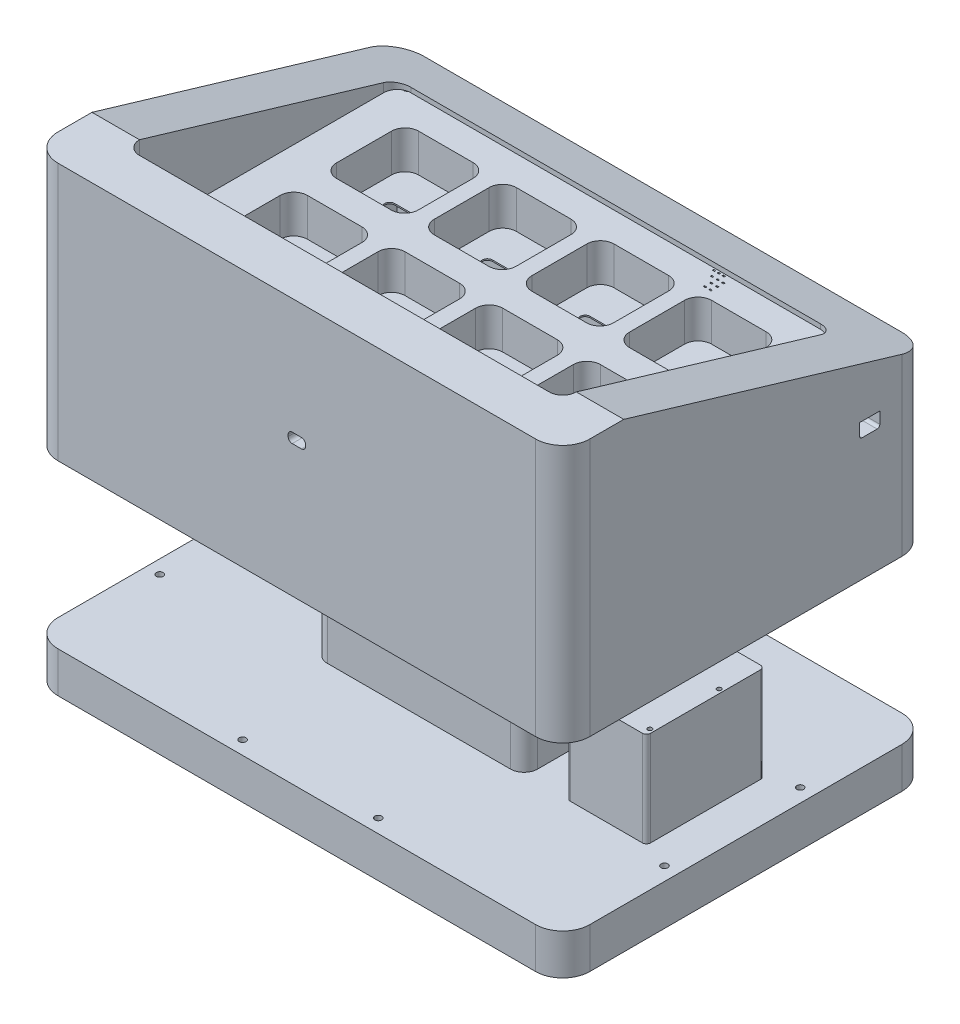
SolidWorks part; units mm, degrees
ref_plane "Front Plane" through (0, 0, 0) normal (0, 0, 1) x (1, 0, 0)
ref_plane "Top Plane" through (0, 0, 0) normal (0, 1, 0) x (1, 0, 0)
ref_plane "Right Plane" through (0, 0, 0) normal (1, 0, 0) x (0, 0, -1)
sketch "Sketch2" plane through (0, 0, 0) normal (0, 1, 0) x (1, 0, 0)
  line L0 (-196, -135) -> (-61, -135)
  line L1 (-196, 135) -> (196, 135)
  line L2 (-196, 135) -> (-196, -135)
  line L3 (-196, -135) -> (196, -135)
  line L4 (196, 135) -> (196, -135)
  line L5 (-196, 135) -> (196, -135) construction
  line L6 (-196, -135) -> (196, 135) construction
  point P0 (0, 0)
  dimension "D1" = 392
  dimension "D2" = 270
  dimension "D3" = 135
extrude "Boss-Extrude1" add sketch "Sketch2" along normal blind 30
sketch "Sketch3" plane through (0, 30, 0) normal (0, 1, 0) x (1, 0, 0)
  line L4 (-196, 135) -> (-196, -135) construction
  line L5 (-196, -30) -> (-196, -135)
  line L6 (-196, -135) -> (-23.5, -135) construction
  line L7 (-196, -135) -> (196, -135) construction
  line L12 (-23.5, -135) -> (-23.5, -85) construction
  line L16 (-77.5, 45) -> (77.5, 45)
  line L17 (-77.5, 45) -> (-77.5, -45)
  line L18 (-77.5, -45) -> (77.5, -45)
  line L19 (77.5, 45) -> (77.5, -45)
  line L20 (-77.5, 45) -> (77.5, -45) construction
  line L21 (-77.5, -45) -> (77.5, 45) construction
  point P5 (0, 0)
  dimension "D1" = 172.5
  dimension "D2" = 155
  dimension "D3" = 50
  dimension "D4" = 90
extrude "Boss-Extrude2" add sketch "Sketch3" along normal blind 70 contours L17 L18 L19 L16
ref_plane "Plane1" through (0, 150, 0) normal (0, 1, 0) x (1, 0, 0)
sketch "Sketch15" plane through (0, 150, 0) normal (0, 1, 0) x (1, 0, 0)
  line L1 (-178.4314, 128.826) -> (178.4314, 128.826)
  line L2 (-178.4314, 128.826) -> (-178.4314, -128.826)
  line L3 (-178.4314, -128.826) -> (178.4314, -128.826)
  line L4 (178.4314, 128.826) -> (178.4314, -128.826)
  line L5 (-178.4314, 128.826) -> (178.4314, -128.826) construction
  line L6 (-178.4314, -128.826) -> (178.4314, 128.826) construction
  point P0 (0, 0)
sketch "Sketch17" plane through (0, 150, 0) normal (0, 1, 0) x (1, 0, 0)
  line L1 (-196, 135) -> (196, 135)
  line L2 (-196, 135) -> (-196, -135)
  line L3 (-196, -135) -> (196, -135)
  line L4 (196, 135) -> (196, -135)
  line L5 (-196, 135) -> (196, -135) construction
  line L6 (-196, -135) -> (196, 135) construction
  point P0 (0, 0)
  dimension "D1" = 392
  dimension "D2" = 270
extrude "Boss-Extrude3" add sketch "Sketch17" along normal blind 190 separate body
sketch "Sketch18" plane through (-196, 0, 0) normal (-1, 0, 0) x (0, 0, 1)
  line L0 (-135.2725, 210.3629) -> (3.9225, 185.819) construction
  line L1 (-135, 340) -> (135, 340) construction
  dimension "D1" = 10
sketch "Sketch19" plane through (-196, 0, 0) normal (-1, 0, 0) x (0, 0, 1)
  line L0 (-135, 340) -> (135, 316.3781)
  line L1 (135, 340) -> (135, 150) construction
  line L2 (135, 316.3781) -> (135, 340)
  line L3 (135, 340) -> (-135, 340)
  dimension "D1" = 5
fillet "Fillet4" radius 20 4 edges at (-196, 245, 135) (196, 245, 135) (196, 245, -135) (-196, 245, -135)
sketch "Sketch41" plane through (0, 0, 0) normal (0, -1, 0) x (1, 0, 0)
  line L0 (0, -135) -> (0, -138.1967) construction
  line L1 (-196, -135) -> (196, -135) construction
sketch "Sketch44" plane through (0, 0, 0) normal (0, -1, 0) x (1, 0, 0)
  line L0 (0, 0) -> (196, 0) construction
  line L1 (196, 115) -> (196, -115) construction
  line L2 (196, 0) -> (-196, 0) construction
  line L3 (-196, -135.2725) -> (-196, 3.9225) construction
  line L4 (0, 135) -> (0, -138.1967) construction
  line L5 (-176, 135) -> (176, 135) construction
sketch "Sketch66" plane through (-196, 0, 0) normal (-1, 0, 0) x (0, 0, 1)
  line L1 (-115, 309.6214) -> (115, 309.6214)
  line L2 (-115, 309.6214) -> (-115, 150)
  line L3 (-115, 150) -> (115, 150)
  line L4 (115, 309.6214) -> (115, 150)
  line L5 (-115, 309.6214) -> (115, 150) construction
  line L6 (-115, 150) -> (115, 309.6214) construction
  point P0 (0, 229.8107)
sketch "Sketch68" plane through (196, 0, 0) normal (1, 0, 0) x (0, 0, -1)
  line L1 (-115, 309.6214) -> (115, 309.6214)
  line L2 (-115, 309.6214) -> (-115, 150)
  line L3 (-115, 150) -> (115, 150)
  line L4 (115, 309.6214) -> (115, 150)
  line L5 (-115, 309.6214) -> (115, 150) construction
  line L6 (-115, 150) -> (115, 309.6214) construction
  point P0 (0, 229.8107)
fillet "Fillet5" radius 10 4 edges at (77.5, 65, 45) (77.5, 65, -45) (-77.5, 65, -45) (-77.5, 65, 45)
sketch "Sketch71" plane through (0, 340, 0) normal (0, 1, 0) x (1, 0, 0)
  line L8 (-161, 100) -> (-161, -100)
  line L9 (-161, -100) -> (161, -100)
  line L10 (161, -100) -> (161, 100)
  line L11 (161, 100) -> (-161, 100)
  line L12 (-161, 90) -> (-161, -90)
  line L13 (-151, -100) -> (151, -100)
  line L14 (161, -90) -> (161, 90)
  line L15 (151, 100) -> (-151, 100)
  arc A4 (-161, -90) -> (-151, -100) centre (-151, -90) ccw
  arc A5 (151, -100) -> (161, -90) centre (151, -90) ccw
  arc A6 (161, 90) -> (151, 100) centre (151, 90) ccw
  arc A7 (-161, 90) -> (-151, 100) centre (-151, 90) cw
  dimension "D2" = 10
  dimension "D1" = 35
extrude "Cut-Extrude1" cut sketch "Sketch71" against normal blind 60
sketch "PCB" plane through (0, 280, 0) normal (0, 1, 0) x (1, 0, 0)
  line L1 (-160, 107.5) -> (160, 107.5)
  line L2 (-160, 107.5) -> (-160, -107.5)
  line L3 (-160, -107.5) -> (160, -107.5)
  line L4 (160, 107.5) -> (160, -107.5)
  line L5 (-160, 107.5) -> (160, -107.5) construction
  line L6 (-160, -107.5) -> (160, 107.5) construction
  point P0 (0, 0)
  dimension "D1" = 320
  dimension "D2" = 215
sketch "Sketch73" plane through (0, 280, 0) normal (0, 1, 0) x (1, 0, 0)
  line L0 (-160, -107.5) -> (-160, -33.357) construction
  line L1 (-160, 107.5) -> (-160, -107.5) construction
  line L2 (-160, -33.357) -> (-110.75, -33.357) construction
  line L3 (-110.75, -33.357) -> (-107, -33.357) construction
  line L4 (-107, -33.357) -> (-96.4, -33.357) construction
  line L5 (-107, -33.357) -> (-117.6, -33.357) construction
  line L6 (-96.4, -33.357) -> (-99.83, -33.357) construction
  line L7 (-117.6, -33.357) -> (-114.17, -33.357) construction
  line L8 (-42.17, -29.627) -> (-27.83, -29.627)
  line L11 (-114.17, -29.627) -> (-99.83, -29.627)
  line L12 (-114.17, -37.087) -> (-99.83, -37.087)
  line L13 (-42.17, -37.087) -> (-27.83, -37.087)
  line L14 (29.83, -29.627) -> (44.17, -29.627)
  line L15 (29.83, -37.087) -> (44.17, -37.087)
  line L16 (101.83, -29.627) -> (116.17, -29.627)
  line L17 (101.83, -37.087) -> (116.17, -37.087)
  line L18 (-114.17, -33.357) -> (-114.17, 7.143) construction
  line L19 (-114.17, 7.143) -> (-161, 7.143) construction
  line L20 (-161, 90) -> (-161, -90) construction
  line L21 (-161, 7.143) -> (161, 7.143) construction
  line L22 (161, -90) -> (161, 90) construction
  line L23 (101.83, 51.373) -> (116.17, 51.373)
  line L24 (101.83, 43.913) -> (116.17, 43.913)
  line L25 (29.83, 51.373) -> (44.17, 51.373)
  line L26 (29.83, 43.913) -> (44.17, 43.913)
  line L27 (-42.17, 51.373) -> (-27.83, 51.373)
  line L28 (-42.17, 43.913) -> (-27.83, 43.913)
  line L29 (-114.17, 51.373) -> (-99.83, 51.373)
  line L30 (-114.17, 43.913) -> (-99.83, 43.913)
  arc A4 (-99.83, -37.087) -> (-99.83, -29.627) centre (-99.83, -33.357) ccw
  arc A5 (-114.17, -29.627) -> (-114.17, -37.087) centre (-114.17, -33.357) ccw
  arc A6 (-27.83, -37.087) -> (-27.83, -29.627) centre (-27.83, -33.357) ccw
  arc A7 (-42.17, -29.627) -> (-42.17, -37.087) centre (-42.17, -33.357) ccw
  arc A8 (44.17, -37.087) -> (44.17, -29.627) centre (44.17, -33.357) ccw
  arc A9 (29.83, -29.627) -> (29.83, -37.087) centre (29.83, -33.357) ccw
  arc A10 (116.17, -37.087) -> (116.17, -29.627) centre (116.17, -33.357) ccw
  arc A11 (101.83, -29.627) -> (101.83, -37.087) centre (101.83, -33.357) ccw
  arc A12 (101.83, 43.913) -> (101.83, 51.373) centre (101.83, 47.643) cw
  arc A13 (116.17, 51.373) -> (116.17, 43.913) centre (116.17, 47.643) cw
  arc A14 (29.83, 43.913) -> (29.83, 51.373) centre (29.83, 47.643) cw
  arc A15 (44.17, 51.373) -> (44.17, 43.913) centre (44.17, 47.643) cw
  arc A16 (-42.17, 43.913) -> (-42.17, 51.373) centre (-42.17, 47.643) cw
  arc A17 (-27.83, 51.373) -> (-27.83, 43.913) centre (-27.83, 47.643) cw
  arc A18 (-114.17, 43.913) -> (-114.17, 51.373) centre (-114.17, 47.643) cw
  arc A19 (-99.83, 51.373) -> (-99.83, 43.913) centre (-99.83, 47.643) cw
  dimension "D3" = 4
  dimension "D1" = 74.143
  dimension "D2" = 49.25
  dimension "D4" = 3.75
  dimension "D5" = 10.6
  dimension "D6" = 10.6
  dimension "D7" = 3.43
  dimension "D8" = 3.43
  dimension "D9" = 40.5
sketch "Sketch75" plane through (0, 280, 0) normal (0, 1, 0) x (1, 0, 0)
  line L0 (-117.6, -33.357) -> (-133.6, -33.357) construction
  line L1 (-160, -33.357) -> (-110.75, -33.357) construction
  line L2 (-96.4, -33.357) -> (-73.4, -33.357) construction
  line L4 (-73.4, -33.357) -> (-133.6, -33.357) construction
  line L5 (-107, -29.627) -> (-107, -3.627) construction
  line L10 (-114.17, -29.627) -> (-99.83, -29.627) construction
  line L11 (-107, -37.087) -> (-107, -64.087) construction
  line L12 (-114.17, -37.087) -> (-99.83, -37.087) construction
  line L13 (-73.4, -33.357) -> (-73.4, -13.627)
  line L14 (-83.4, -3.627) -> (-107, -3.627)
  line L15 (-107, -3.627) -> (-123.6, -3.627)
  line L16 (-133.6, -13.627) -> (-133.6, -33.357)
  line L17 (-133.6, -33.357) -> (-133.6, -54.087)
  line L18 (-123.6, -64.087) -> (-107, -64.087)
  line L19 (-107, -64.087) -> (-83.4, -64.087)
  line L20 (-73.4, -54.087) -> (-73.4, -33.357)
  line L21 (-1.4, -54.087) -> (-1.4, -33.357)
  line L22 (-1.4, -33.357) -> (-1.4, -13.627)
  line L23 (-11.4, -3.627) -> (-35, -3.627)
  line L24 (-35, -3.627) -> (-51.6, -3.627)
  line L25 (-61.6, -13.627) -> (-61.6, -33.357)
  line L26 (-61.6, -33.357) -> (-61.6, -54.087)
  line L27 (-51.6, -64.087) -> (-35, -64.087)
  line L28 (-35, -64.087) -> (-11.4, -64.087)
  line L29 (70.6, -54.087) -> (70.6, -33.357)
  line L30 (70.6, -33.357) -> (70.6, -13.627)
  line L31 (60.6, -3.627) -> (37, -3.627)
  line L32 (37, -3.627) -> (20.4, -3.627)
  line L33 (10.4, -13.627) -> (10.4, -33.357)
  line L34 (10.4, -33.357) -> (10.4, -54.087)
  line L35 (20.4, -64.087) -> (37, -64.087)
  line L36 (37, -64.087) -> (60.6, -64.087)
  line L37 (142.6, -54.087) -> (142.6, -33.357)
  line L38 (142.6, -33.357) -> (142.6, -13.627)
  line L39 (132.6, -3.627) -> (109, -3.627)
  line L40 (109, -3.627) -> (92.4, -3.627)
  line L41 (82.4, -13.627) -> (82.4, -33.357)
  line L42 (82.4, -33.357) -> (82.4, -54.087)
  line L43 (92.4, -64.087) -> (109, -64.087)
  line L44 (109, -64.087) -> (132.6, -64.087)
  line L45 (-161, 7.143) -> (161, 7.143) construction
  line L46 (109, 78.373) -> (132.6, 78.373)
  line L47 (92.4, 78.373) -> (109, 78.373)
  line L48 (82.4, 47.643) -> (82.4, 68.373)
  line L49 (82.4, 27.913) -> (82.4, 47.643)
  line L50 (109, 17.913) -> (92.4, 17.913)
  line L51 (132.6, 17.913) -> (109, 17.913)
  line L52 (142.6, 47.643) -> (142.6, 27.913)
  line L53 (142.6, 68.373) -> (142.6, 47.643)
  line L54 (37, 78.373) -> (60.6, 78.373)
  line L55 (20.4, 78.373) -> (37, 78.373)
  line L56 (10.4, 47.643) -> (10.4, 68.373)
  line L57 (10.4, 27.913) -> (10.4, 47.643)
  line L58 (37, 17.913) -> (20.4, 17.913)
  line L59 (60.6, 17.913) -> (37, 17.913)
  line L60 (70.6, 47.643) -> (70.6, 27.913)
  line L61 (70.6, 68.373) -> (70.6, 47.643)
  line L62 (-35, 78.373) -> (-11.4, 78.373)
  line L63 (-51.6, 78.373) -> (-35, 78.373)
  line L64 (-61.6, 47.643) -> (-61.6, 68.373)
  line L65 (-61.6, 27.913) -> (-61.6, 47.643)
  line L66 (-35, 17.913) -> (-51.6, 17.913)
  line L67 (-11.4, 17.913) -> (-35, 17.913)
  line L68 (-1.4, 47.643) -> (-1.4, 27.913)
  line L69 (-1.4, 68.373) -> (-1.4, 47.643)
  line L70 (-107, 78.373) -> (-83.4, 78.373)
  line L71 (-123.6, 78.373) -> (-107, 78.373)
  line L72 (-133.6, 47.643) -> (-133.6, 68.373)
  line L73 (-133.6, 27.913) -> (-133.6, 47.643)
  line L74 (-107, 17.913) -> (-123.6, 17.913)
  line L75 (-83.4, 17.913) -> (-107, 17.913)
  line L76 (-73.4, 47.643) -> (-73.4, 27.913)
  line L77 (-73.4, 68.373) -> (-73.4, 47.643)
  arc A0 (-73.4, -13.627) -> (-83.4, -3.627) centre (-83.4, -13.627) ccw
  arc A1 (-123.6, -3.627) -> (-133.6, -13.627) centre (-123.6, -13.627) ccw
  arc A2 (-133.6, -54.087) -> (-123.6, -64.087) centre (-123.6, -54.087) ccw
  arc A3 (-83.4, -64.087) -> (-73.4, -54.087) centre (-83.4, -54.087) ccw
  arc A4 (-11.4, -64.087) -> (-1.4, -54.087) centre (-11.4, -54.087) ccw
  arc A5 (-1.4, -13.627) -> (-11.4, -3.627) centre (-11.4, -13.627) ccw
  arc A6 (-51.6, -3.627) -> (-61.6, -13.627) centre (-51.6, -13.627) ccw
  arc A7 (-61.6, -54.087) -> (-51.6, -64.087) centre (-51.6, -54.087) ccw
  arc A8 (60.6, -64.087) -> (70.6, -54.087) centre (60.6, -54.087) ccw
  arc A9 (70.6, -13.627) -> (60.6, -3.627) centre (60.6, -13.627) ccw
  arc A10 (20.4, -3.627) -> (10.4, -13.627) centre (20.4, -13.627) ccw
  arc A11 (10.4, -54.087) -> (20.4, -64.087) centre (20.4, -54.087) ccw
  arc A12 (132.6, -64.087) -> (142.6, -54.087) centre (132.6, -54.087) ccw
  arc A13 (142.6, -13.627) -> (132.6, -3.627) centre (132.6, -13.627) ccw
  arc A14 (92.4, -3.627) -> (82.4, -13.627) centre (92.4, -13.627) ccw
  arc A15 (82.4, -54.087) -> (92.4, -64.087) centre (92.4, -54.087) ccw
  arc A16 (132.6, 78.373) -> (142.6, 68.373) centre (132.6, 68.373) cw
  arc A17 (82.4, 68.373) -> (92.4, 78.373) centre (92.4, 68.373) cw
  arc A18 (92.4, 17.913) -> (82.4, 27.913) centre (92.4, 27.913) cw
  arc A19 (142.6, 27.913) -> (132.6, 17.913) centre (132.6, 27.913) cw
  arc A20 (60.6, 78.373) -> (70.6, 68.373) centre (60.6, 68.373) cw
  arc A21 (10.4, 68.373) -> (20.4, 78.373) centre (20.4, 68.373) cw
  arc A22 (20.4, 17.913) -> (10.4, 27.913) centre (20.4, 27.913) cw
  arc A23 (70.6, 27.913) -> (60.6, 17.913) centre (60.6, 27.913) cw
  arc A24 (-11.4, 78.373) -> (-1.4, 68.373) centre (-11.4, 68.373) cw
  arc A25 (-61.6, 68.373) -> (-51.6, 78.373) centre (-51.6, 68.373) cw
  arc A26 (-51.6, 17.913) -> (-61.6, 27.913) centre (-51.6, 27.913) cw
  arc A27 (-1.4, 27.913) -> (-11.4, 17.913) centre (-11.4, 27.913) cw
  arc A28 (-133.6, 68.373) -> (-123.6, 78.373) centre (-123.6, 68.373) cw
  arc A29 (-123.6, 17.913) -> (-133.6, 27.913) centre (-123.6, 27.913) cw
  arc A30 (-73.4, 27.913) -> (-83.4, 17.913) centre (-83.4, 27.913) cw
  arc A31 (-83.4, 78.373) -> (-73.4, 68.373) centre (-83.4, 68.373) cw
  point P8 (-110.75, -33.357)
  dimension "D5" = 10
  dimension "D1" = 16
  dimension "D2" = 23
  dimension "D3" = 26
  dimension "D4" = 27
  dimension "D6" = 4
sketch "Sketch76" plane through (0, 280, 0) normal (0, 1, 0) x (1, 0, 0)
  line L0 (-107, -3.627) -> (-107, 17.913) construction
extrude "Cut-Extrude2" cut sketch "Sketch75" against normal blind 28
sketch "Sketch79" plane through (-161, 0, 0) normal (1, 0, 0) x (0, 0, -1)
  line L2 (90, 340) -> (-90, 340)
  line L3 (90, 340) -> (175.4447, 340)
  line L5 (175.4447, 261.0721) -> (175.4447, 340)
  line L6 (-90, 340) -> (175.4447, 261.0721)
sketch "Sketch90" plane through (-196, 0, 0) normal (-1, 0, 0) x (0, 0, 1)
  line L14 (-115, 340) -> (-115, 150)
  line L15 (-115, 150) -> (115, 150)
  line L16 (115, 150) -> (115, 340)
  line L17 (115, 340) -> (-115, 340)
  line L20 (-115, 340) -> (-115, 150)
  line L21 (-115, 150) -> (115, 150)
  line L22 (115, 150) -> (115, 340)
  line L23 (115, 340) -> (-115, 340)
  dimension "D1" = 0
extrude "Cut-Extrude11" cut sketch "Sketch73" against normal blind 31
sketch "Sketch101" plane through (0, 150, 0) normal (0, -1, 0) x (1, 0, 0)
  line L8 (176, 115) -> (-176, 115)
  line L9 (-176, 115) -> (-176, -115)
  line L10 (-176, -115) -> (176, -115)
  line L11 (176, -115) -> (176, 115)
  line L12 (176, 115) -> (-176, 115)
  line L13 (-176, 115) -> (-176, -115)
  line L14 (-176, -115) -> (176, -115)
  line L15 (176, -115) -> (176, 115)
  dimension "D1" = 20
extrude "Cut-Extrude12" cut sketch "Sketch101" against normal blind 101
sketch "Sketch103" plane through (-196, 0, 0) normal (-1, 0, 0) x (0, 0, 1)
  line L14 (-115, 340) -> (-115, 150)
  line L15 (-115, 150) -> (115, 150)
  line L16 (115, 150) -> (115, 340)
  line L17 (115, 340) -> (-115, 340)
  line L20 (-115, 340) -> (-115, 150)
  line L21 (-115, 150) -> (115, 150)
  line L22 (115, 150) -> (115, 340)
  line L23 (115, 340) -> (-115, 340)
  dimension "D1" = 0
sketch "Sketch107" plane through (0, 280, 0) normal (0, 1, 0) x (1, 0, 0)
  line L0 (160, 107.5) -> (154.452, 107.5) construction
  line L1 (154.452, 107.5) -> (154.452, 102.42) construction
  line L2 (160, 107.5) -> (-154.92, 107.5) construction
  line L3 (154.452, 102.42) -> (-154.92, 101.3432) construction
  line L4 (-154.92, 107.5) -> (-154.92, -102.304) construction
  line L5 (154.452, 107.5) -> (154.452, -101.796) construction
  circle A0 centre (154.452, 102.42) radius 2.5
  circle A1 centre (-154.92, 101.3432) radius 2.5
  circle A2 centre (-154.92, -102.304) radius 2.5
  circle A3 centre (154.452, -101.796) radius 2.5
  dimension "D3" = 5
  dimension "D5" = 5
  dimension "D7" = 5
  dimension "D9" = 5
  dimension "D1" = 5.548
  dimension "D2" = 5.08
  dimension "D4" = 314.92
  dimension "D6" = 209.804
  dimension "D8" = 209.296
extrude "Cut-Extrude14" cut sketch "Sketch107" against normal blind 30 contours A3 | A2 | A1 | A0
sketch "Sketch118" plane through (196, 0, 0) normal (1, 0, 0) x (0, 0, -1)
  line L11 (115, 340) -> (-115, 340)
  line L12 (-115, 340) -> (-115, 150)
  line L13 (-115, 150) -> (115, 150)
  line L14 (115, 150) -> (115, 340)
  line L16 (115, 340) -> (-115, 340)
  line L17 (-115, 340) -> (-115, 150)
  line L18 (-115, 150) -> (115, 150)
  line L19 (115, 150) -> (115, 340)
  dimension "D1" = 0
fillet "Fillet6" radius 20 4 edges at (-196, 15, 135) (-196, 15, -135) (196, 15, -135) (196, 15, 135)
sketch "Sketch121" plane through (0, 150, 0) normal (0, -1, 0) x (1, 0, 0)
  line L0 (0, -115) -> (0, -135) construction
  line L1 (-176, -115) -> (176, -115) construction
  line L2 (176, -135) -> (-176, -135) construction
sketch "Sketch126" plane through (0, 150, 0) normal (0, -1, 0) x (1, 0, 0)
  line L0 (0, 135) -> (0, 115) construction
  line L1 (-176, 135) -> (176, 135) construction
  line L2 (176, 115) -> (-176, 115) construction
  line L4 (-22.5, 130) -> (22.5, 130)
  line L5 (-22.5, 130) -> (-22.5, 120)
  line L6 (-22.5, 120) -> (22.5, 120)
  line L7 (22.5, 130) -> (22.5, 120)
  line L8 (-22.5, 130) -> (22.5, 120) construction
  line L9 (-22.5, 120) -> (22.5, 130) construction
  point P6 (0, 125)
  dimension "D1" = 45
  dimension "D2" = 10
sketch "Sketch127" plane through (0, 150, 0) normal (0, -1, 0) x (1, 0, 0)
  line L0 (0, -115) -> (0, -135) construction
  line L1 (-176, -115) -> (176, -115) construction
  line L2 (176, -135) -> (-176, -135) construction
  line L4 (-22.5, -120) -> (22.5, -120)
  line L5 (-22.5, -120) -> (-22.5, -130)
  line L6 (-22.5, -130) -> (22.5, -130)
  line L7 (22.5, -120) -> (22.5, -130)
  line L8 (-22.5, -120) -> (22.5, -130) construction
  line L9 (-22.5, -130) -> (22.5, -120) construction
  point P6 (0, -125)
  dimension "D1" = 45
  dimension "D2" = 10
sketch "Sketch128" plane through (0, 150, 0) normal (0, -1, 0) x (1, 0, 0)
  line L0 (196, 0) -> (176, 0) construction
  line L1 (196, 115) -> (196, -115) construction
  line L2 (176, -115) -> (176, 115) construction
  line L4 (181, 22.5) -> (191, 22.5)
  line L5 (181, 22.5) -> (181, -22.5)
  line L6 (181, -22.5) -> (191, -22.5)
  line L7 (191, 22.5) -> (191, -22.5)
  line L8 (181, 22.5) -> (191, -22.5) construction
  line L9 (181, -22.5) -> (191, 22.5) construction
  point P6 (186, 0)
  dimension "D1" = 45
  dimension "D2" = 10
sketch "Sketch129" plane through (0, 30, 0) normal (0, 1, 0) x (1, 0, 0)
  line L0 (196, 0) -> (156.4046, 0) construction
  line L1 (196, 115) -> (196, -115) construction
  line L2 (196, 0) -> (176, 0) construction
  line L8 (181, 22.5) -> (191, 22.5)
  line L9 (196, 0) -> (176, 0) construction
  line L10 (196, 0) -> (186, 0) construction
  line L11 (181, 22.5) -> (181, -22.5)
  line L12 (181, -22.5) -> (191, -22.5)
  line L13 (191, 22.5) -> (191, -22.5)
  line L14 (181, 22.5) -> (191, -22.5) construction
  line L15 (181, -22.5) -> (191, 22.5) construction
  point P5 (176.2023, 0)
  dimension "D1" = 10
  dimension "D2" = 45
  dimension "D3" = 20
  dimension "D4" = 10
sketch "Sketch130" plane through (0, 30, 0) normal (0, 1, 0) x (1, 0, 0)
  line L0 (0, 135) -> (0, 115) construction
  line L1 (-176, 135) -> (176, 135) construction
  line L2 (0, -148.5) -> (0, 148.5) construction
  dimension "D1" = 20
sketch "Sketch131" plane through (0, 30, 0) normal (0, 1, 0) x (1, 0, 0)
  line L0 (0, 135) -> (0, 115) construction
  line L1 (-22.5, 130) -> (22.5, 130)
  line L2 (-22.5, 130) -> (-22.5, 120)
  line L3 (-22.5, 120) -> (22.5, 120)
  line L4 (22.5, 130) -> (22.5, 120)
  line L5 (-22.5, 130) -> (22.5, 120) construction
  line L6 (-22.5, 120) -> (22.5, 130) construction
  point P0 (0, 125)
  dimension "D1" = 45
  dimension "D2" = 10
sketch "Sketch132" plane through (0, 30, 0) normal (0, 1, 0) x (1, 0, 0)
  line L0 (0, -135) -> (0, -115) construction
  line L1 (-176, -135) -> (176, -135) construction
  line L2 (0, -148.5) -> (0, 148.5) construction
  line L4 (-22.5, -120) -> (22.5, -120)
  line L5 (-22.5, -120) -> (-22.5, -130)
  line L6 (-22.5, -130) -> (22.5, -130)
  line L7 (22.5, -120) -> (22.5, -130)
  line L8 (-22.5, -120) -> (22.5, -130) construction
  line L9 (-22.5, -130) -> (22.5, -120) construction
  point P7 (0, -125)
  dimension "D1" = 20
  dimension "D2" = 45
  dimension "D3" = 10
sketch "Sketch138" plane through (196, 0, 0) normal (1, 0, 0) x (0, 0, -1)
  line L11 (115, 340) -> (-115, 340)
  line L12 (-115, 340) -> (-115, 150)
  line L13 (-115, 150) -> (115, 150)
  line L14 (115, 150) -> (115, 340)
  line L16 (115, 340) -> (-115, 340)
  line L17 (-115, 340) -> (-115, 150)
  line L18 (-115, 150) -> (115, 150)
  line L19 (115, 150) -> (115, 340)
  dimension "D1" = 0
sketch "Sketch141" plane through (0, 251, 0) normal (0, -1, 0) x (1, 0, 0)
  line L1 (-160, 107.5) -> (160, 107.5)
  line L2 (-160, 107.5) -> (-160, -107.5)
  line L3 (-160, -107.5) -> (160, -107.5)
  line L4 (160, 107.5) -> (160, -107.5)
  line L5 (-160, 107.5) -> (160, -107.5) construction
  line L6 (-160, -107.5) -> (160, 107.5) construction
  point P0 (0, 0)
  dimension "D1" = 320
  dimension "D2" = 215
sketch "Sketch142" plane through (0, 251, 0) normal (0, -1, 0) x (1, 0, 0)
  line L0 (-160, -107.5) -> (151.864, -107.5) construction
  line L1 (-160, -107.5) -> (160, -107.5) construction
  line L2 (151.864, -107.5) -> (151.864, -92.786) construction
  line L3 (151.864, -92.786) -> (151.864, -86.686) construction
  dimension "D1" = 311.864
  dimension "D2" = 14.714
  dimension "D3" = 6.1
sketch "Sketch144" plane through (196, 0, 0) normal (1, 0, 0) x (0, 0, -1)
  line L0 (92.786, 251) -> (86.686, 251)
  line L1 (107.5, 251) -> (92.786, 251) construction
  line L2 (92.786, 251) -> (86.686, 251) construction
  line L4 (89.736, 251) -> (89.736, 244.9)
  line L5 (86.686, 251) -> (92.786, 251)
  line L6 (86.686, 251) -> (86.686, 244.9)
  line L7 (86.686, 244.9) -> (92.786, 244.9)
  line L8 (92.786, 251) -> (92.786, 244.9)
  line L9 (86.686, 251) -> (92.786, 244.9) construction
  line L10 (86.686, 244.9) -> (92.786, 251) construction
  point P7 (89.736, 247.95)
  dimension "D1" = 6.1
extrude "Cut-Extrude25" cut sketch "Sketch144" against normal blind 20 contours L8 L0 L4 L7
sketch "Sketch145" plane through (0, 280, 0) normal (0, 1, 0) x (1, 0, 0)
  line L0 (-61.6, -33.857) -> (-73.4, -33.857) construction
  line L1 (-61.6, -13.627) -> (-61.6, -54.087) construction
  line L2 (-73.4, -54.087) -> (-73.4, -13.627) construction
extrude "Cut-Extrude27" cut sketch "Sketch79" against normal blind 35 and the other way blind 370 contours L5 L3 L2 L6
sketch "Sketch150" plane through (0, 0, 0) normal (0, -1, 0) x (1, 0, 0)
  line L8 (176, 135) -> (-176, 135)
  line L9 (-196, 115) -> (-196, -115)
  line L10 (-176, -135) -> (176, -135)
  line L11 (196, -115) -> (196, 115)
  line L12 (176, 135) -> (-176, 135)
  line L13 (-196, 115) -> (-196, -115)
  line L14 (-176, -135) -> (176, -135)
  line L15 (196, -115) -> (196, 115)
  arc A8 (-176, 135) -> (-196, 115) centre (-176, 115) ccw
  arc A9 (-196, -115) -> (-176, -135) centre (-176, -115) ccw
  arc A10 (176, -135) -> (196, -115) centre (176, -115) ccw
  arc A11 (196, 115) -> (176, 135) centre (176, 115) ccw
  arc A12 (-176, 135) -> (-196, 115) centre (-176, 115) ccw
  arc A13 (-196, -115) -> (-176, -135) centre (-176, -115) ccw
  arc A14 (176, -135) -> (196, -115) centre (176, -115) ccw
  arc A15 (196, 115) -> (176, 135) centre (176, 115) ccw
  dimension "D1" = 0
extrude "Boss-Extrude12" add sketch "Sketch150" against normal blind 30
sketch "Sketch151" plane through (0, 100, 0) normal (0, 1, 0) x (1, 0, 0)
  line L8 (-67.5, -38) -> (67.5, -38)
  line L9 (70.5, -35) -> (70.5, 35)
  line L10 (67.5, 38) -> (-67.5, 38)
  line L11 (-70.5, 35) -> (-70.5, -35)
  line L12 (-67.5, -38) -> (67.5, -38)
  line L13 (70.5, -35) -> (70.5, 35)
  line L14 (67.5, 38) -> (-67.5, 38)
  line L15 (-70.5, 35) -> (-70.5, -35)
  arc A8 (67.5, -38) -> (70.5, -35) centre (67.5, -35) ccw
  arc A9 (70.5, 35) -> (67.5, 38) centre (67.5, 35) ccw
  arc A10 (-67.5, 38) -> (-70.5, 35) centre (-67.5, 35) ccw
  arc A11 (-70.5, -35) -> (-67.5, -38) centre (-67.5, -35) ccw
  arc A12 (67.5, -38) -> (70.5, -35) centre (67.5, -35) ccw
  arc A13 (70.5, 35) -> (67.5, 38) centre (67.5, 35) ccw
  arc A14 (-67.5, 38) -> (-70.5, 35) centre (-67.5, 35) ccw
  arc A15 (-70.5, -35) -> (-67.5, -38) centre (-67.5, -35) ccw
  dimension "D1" = 7
extrude "Cut-Extrude29" cut sketch "Sketch151" against normal blind 70
sketch "Sketch153" plane through (-196, 0, 0) normal (-1, 0, 0) x (0, 0, 1)
  line L10 (90, 340) -> (-115, 279.0448)
  line L11 (-115, 279.0448) -> (-115, 150)
  line L12 (-115, 150) -> (115, 150)
  line L13 (115, 150) -> (115, 340)
  line L14 (115, 340) -> (90, 340)
  line L16 (-115, 279.0448) -> (-115, 150)
  line L17 (-115, 150) -> (115, 150)
  line L18 (115, 150) -> (115, 340)
  line L19 (115, 340) -> (90, 340)
  line L21 (90, 340) -> (-115, 279.0448)
  dimension "D1" = 0
sketch "Sketch156" plane through (0, 251, 0) normal (0, -1, 0) x (1, 0, 0)
  line L0 (-160, -107.5) -> (4.325, -107.5) construction
  line L1 (-160, -107.5) -> (151.864, -107.5) construction
  line L2 (4.325, -107.5) -> (4.325, 103.828) construction
  line L3 (4.325, 103.828) -> (-4.33, 103.828) construction
  dimension "D1" = 164.325
  dimension "D2" = 211.328
  dimension "D3" = 8.655
sketch "Sketch212" plane through (196, 0, 0) normal (1, 0, 0) x (0, 0, -1)
sketch "Sketch164" plane through (0, 0, 135) normal (0, 0, 1) x (1, 0, 0)
  line L0 (-160, 251) -> (151.864, 251) construction
  line L1 (50.169, 327.4846) -> (144.6904, 327.4846)
  line L2 (50.169, 327.4846) -> (50.169, 251)
  line L3 (50.169, 251) -> (144.6904, 251)
  line L4 (144.6904, 327.4846) -> (144.6904, 251)
  line L5 (50.169, 327.4846) -> (144.6904, 251) construction
  line L6 (50.169, 251) -> (144.6904, 327.4846) construction
  point P0 (97.4297, 289.2423)
sketch "Sketch173" plane through (196, 0, 0) normal (1, 0, 0) x (0, 0, -1)
  line L0 (92.786, 251) -> (92.786, 244.9) construction
  line L3 (89.736, 244.9) -> (92.786, 244.9) construction
  line L4 (92.786, 244.9) -> (91.261, 244.9) construction
  line L5 (91.261, 244.9) -> (91.261, 251) construction
  line L6 (-115, 251) -> (115, 251) construction
  line L7 (91.261, 247.95) -> (71.3065, 247.95) construction
  line L8 (83.761, 252.95) -> (98.761, 252.95)
  line L9 (83.761, 252.95) -> (83.761, 242.95)
  line L10 (83.761, 242.95) -> (98.761, 242.95)
  line L11 (98.761, 252.95) -> (98.761, 242.95)
  line L12 (83.761, 252.95) -> (98.761, 242.95) construction
  line L13 (83.761, 242.95) -> (98.761, 252.95) construction
  line L14 (71.3065, 247.95) -> (71.3065, 270.4248)
  line L15 (71.3065, 270.4248) -> (113.4758, 270.4248)
  line L16 (113.4758, 270.4248) -> (113.4758, 232.0158)
  line L17 (113.4758, 232.0158) -> (71.3065, 232.0158)
  line L18 (71.3065, 232.0158) -> (71.3065, 247.95)
  point P5 (91.261, 247.95)
  dimension "D1" = 15
  dimension "D2" = 10
extrude "Boss-Extrude13" add sketch "Sketch173" against normal blind 20
sketch "Sketch174" plane through (196, 0, 0) normal (1, 0, 0) x (0, 0, -1)
  line L0 (91.261, 244.9) -> (91.261, 251) construction
  line L1 (89.736, 244.9) -> (92.786, 244.9) construction
  line L2 (-115, 251) -> (115, 251) construction
  line L4 (83.761, 255.45) -> (98.761, 255.45)
  line L5 (83.761, 255.45) -> (83.761, 240.45)
  line L6 (83.761, 240.45) -> (98.761, 240.45)
  line L7 (98.761, 255.45) -> (98.761, 240.45)
  line L8 (83.761, 255.45) -> (98.761, 240.45) construction
  line L9 (83.761, 240.45) -> (98.761, 255.45) construction
  point P8 (91.261, 247.95)
  dimension "D1" = 15
  dimension "D2" = 15
extrude "Cut-Extrude37" cut sketch "Sketch174" against normal blind 20
fillet "Fillet8" radius 2 4 edges at (186, 255.45, -98.761) (186, 240.45, -98.761) (186, 240.45, -83.761) (186, 255.45, -83.761)
sketch "Sketch176" plane through (196, 0, 0) normal (1, 0, 0) x (0, 0, -1)
  line L1 (-28.7444, 249) -> (-28.7444, 276.3202)
  line L2 (-28.7444, 276.3202) -> (-112.8671, 276.3202)
  line L3 (-112.8671, 276.3202) -> (-115, 276.3202)
  line L4 (-115, 340) -> (-115, 150) construction
  line L5 (-115, 276.3202) -> (-115, 239.0651)
  line L6 (-115, 239.0651) -> (-28.7444, 239.0651)
  line L7 (-28.7444, 239.0651) -> (-28.7444, 249)
sketch "Sketch182" plane through (-196, 0, 0) normal (-1, 0, 0) x (0, 0, 1)
  line L0 (115, 238.6376) -> (18.5121, 238.6376) construction
  line L1 (115, 150) -> (115, 340) construction
  line L2 (18.5121, 238.6376) -> (18.5121, 269.2314) construction
  line L3 (18.5121, 269.2314) -> (115, 269.2314) construction
  line L4 (115, 269.2314) -> (115, 238.6376) construction
ref_plane "Plane2" through (210, 0, 0) normal (1, 0, 0) x (0, 0, -1)
sketch "Sketch202" plane through (176, 0, 0) normal (1, 0, 0) x (0, 0, -1)
  line L8 (98.761, 251) -> (98.761, 253.45)
  line L9 (96.761, 255.45) -> (85.761, 255.45)
  line L10 (83.761, 253.45) -> (83.761, 251)
  line L11 (83.761, 251) -> (98.761, 251)
  line L12 (98.761, 251) -> (98.761, 253.45)
  line L13 (96.761, 255.45) -> (85.761, 255.45)
  line L14 (83.761, 253.45) -> (83.761, 251)
  line L15 (83.761, 251) -> (98.761, 251)
  arc A4 (98.761, 253.45) -> (96.761, 255.45) centre (96.761, 253.45) ccw
  arc A5 (85.761, 255.45) -> (83.761, 253.45) centre (85.761, 253.45) ccw
  arc A6 (98.761, 253.45) -> (96.761, 255.45) centre (96.761, 253.45) ccw
  arc A7 (85.761, 255.45) -> (83.761, 253.45) centre (85.761, 253.45) ccw
  dimension "D1" = 0
extrude "Boss-Extrude24" add sketch "Sketch202" along normal blind 20
sketch "Sketch203" plane through (0, 251, 0) normal (0, -1, 0) x (1, 0, 0)
  line L0 (-160, -37.4195) -> (-176, -37.4195) construction
  line L1 (-160, 107.5) -> (160, 107.5)
  line L2 (-160, 107.5) -> (-160, -107.5)
  line L3 (-160, -107.5) -> (160, -107.5)
  line L4 (160, 107.5) -> (160, -107.5)
  line L5 (-160, 107.5) -> (160, -107.5) construction
  line L6 (-160, -107.5) -> (160, 107.5) construction
  line L7 (-176, 115) -> (-176, -115) construction
  point P0 (0, 0)
  dimension "D1" = 320
  dimension "D2" = 215
sketch "Sketch209" plane through (0, 251, 0) normal (0, -1, 0) x (1, 0, 0)
  line L0 (-160, -107.5) -> (74.188, -107.5) construction
  line L1 (-160, -107.5) -> (160, -107.5) construction
  line L2 (74.188, -107.5) -> (74.188, -98.356) construction
  line L3 (-160, -107.5) -> (77.744, -107.5) construction
  line L4 (73.388, -97.856) -> (74.988, -97.856)
  line L5 (73.388, -97.856) -> (73.388, -98.856)
  line L6 (73.388, -98.856) -> (74.988, -98.856)
  line L7 (74.988, -97.856) -> (74.988, -98.856)
  line L8 (73.388, -97.856) -> (74.988, -98.856) construction
  line L9 (73.388, -98.856) -> (74.988, -97.856) construction
  line L10 (77.744, -107.5) -> (77.744, -98.356) construction
  line L11 (-160, -107.5) -> (81.3, -107.5) construction
  line L12 (76.944, -97.856) -> (78.544, -97.856)
  line L13 (76.944, -97.856) -> (76.944, -98.856)
  line L14 (76.944, -98.856) -> (78.544, -98.856)
  line L15 (78.544, -97.856) -> (78.544, -98.856)
  line L16 (76.944, -97.856) -> (78.544, -98.856) construction
  line L17 (76.944, -98.856) -> (78.544, -97.856) construction
  line L18 (81.3, -107.5) -> (81.3, -98.356) construction
  line L19 (-160, -107.5) -> (77.236, -107.5) construction
  line L20 (80.5, -97.856) -> (82.1, -97.856)
  line L21 (80.5, -97.856) -> (80.5, -98.856)
  line L22 (80.5, -98.856) -> (82.1, -98.856)
  line L23 (82.1, -97.856) -> (82.1, -98.856)
  line L24 (80.5, -97.856) -> (82.1, -98.856) construction
  line L25 (80.5, -98.856) -> (82.1, -97.856) construction
  line L26 (77.236, -107.5) -> (77.236, -93.784) construction
  line L27 (-160, -107.5) -> (81.506, -107.5) construction
  line L28 (76.436, -93.284) -> (78.036, -93.284)
  line L29 (76.436, -93.284) -> (76.436, -94.284)
  line L30 (76.436, -94.284) -> (78.036, -94.284)
  line L31 (78.036, -93.284) -> (78.036, -94.284)
  line L32 (76.436, -93.284) -> (78.036, -94.284) construction
  line L33 (76.436, -94.284) -> (78.036, -93.284) construction
  line L34 (81.506, -107.5) -> (81.506, -93.784) construction
  line L35 (-160, -107.5) -> (85.666, -107.5) construction
  line L36 (80.706, -93.284) -> (82.306, -93.284)
  line L37 (80.706, -93.284) -> (80.706, -94.284)
  line L38 (80.706, -94.284) -> (82.306, -94.284)
  line L39 (82.306, -93.284) -> (82.306, -94.284)
  line L40 (80.706, -93.284) -> (82.306, -94.284) construction
  line L41 (80.706, -94.284) -> (82.306, -93.284) construction
  line L42 (85.666, -107.5) -> (85.666, -93.784) construction
  line L43 (-160, -107.5) -> (85.57, -107.5) construction
  line L44 (84.866, -93.284) -> (86.466, -93.284)
  line L45 (84.866, -93.284) -> (84.866, -94.284)
  line L46 (84.866, -94.284) -> (86.466, -94.284)
  line L47 (86.466, -93.284) -> (86.466, -94.284)
  line L48 (84.866, -93.284) -> (86.466, -94.284) construction
  line L49 (84.866, -94.284) -> (86.466, -93.284) construction
  line L50 (85.666, -107.5) -> (85.666, -89.212) construction
  line L51 (-160, -107.5) -> (85.364, -107.5) construction
  line L52 (84.866, -88.712) -> (86.466, -88.712)
  line L53 (84.866, -88.712) -> (84.866, -89.712)
  line L54 (84.866, -89.712) -> (86.466, -89.712)
  line L55 (86.466, -88.712) -> (86.466, -89.712)
  line L56 (84.866, -88.712) -> (86.466, -89.712) construction
  line L57 (84.866, -89.712) -> (86.466, -88.712) construction
  line L58 (85.364, -107.5) -> (85.364, -84.64) construction
  line L59 (-160, -107.5) -> (81.3, -107.5) construction
  line L60 (84.564, -84.14) -> (86.164, -84.14)
  line L61 (84.564, -84.14) -> (84.564, -85.14)
  line L62 (84.564, -85.14) -> (86.164, -85.14)
  line L63 (86.164, -84.14) -> (86.164, -85.14)
  line L64 (84.564, -84.14) -> (86.164, -85.14) construction
  line L65 (84.564, -85.14) -> (86.164, -84.14) construction
  line L66 (81.3, -107.5) -> (81.3, -89.212) construction
  line L67 (81.3, -107.5) -> (81.3, -84.64) construction
  line L68 (80.5, -88.712) -> (82.1, -88.712)
  line L69 (80.5, -88.712) -> (80.5, -89.712)
  line L70 (80.5, -89.712) -> (82.1, -89.712)
  line L71 (82.1, -88.712) -> (82.1, -89.712)
  line L72 (80.5, -88.712) -> (82.1, -89.712) construction
  line L73 (80.5, -89.712) -> (82.1, -88.712) construction
  line L75 (80.5, -84.14) -> (82.1, -84.14)
  line L76 (80.5, -84.14) -> (80.5, -85.14)
  line L77 (80.5, -85.14) -> (82.1, -85.14)
  line L78 (82.1, -84.14) -> (82.1, -85.14)
  line L79 (80.5, -84.14) -> (82.1, -85.14) construction
  line L80 (80.5, -85.14) -> (82.1, -84.14) construction
  dimension "D1" = 234.188
  dimension "D2" = 9.144
  dimension "D3" = 1.6
  dimension "D4" = 1
  dimension "D5" = 237.744
  dimension "D6" = 1
  dimension "D7" = 1.6
  dimension "D8" = 241.3
  dimension "D9" = 1.6
  dimension "D10" = 237.236
  dimension "D11" = 13.716
  dimension "D12" = 1
  dimension "D13" = 1.6
  dimension "D14" = 241.506
  dimension "D15" = 1.6
  dimension "D16" = 245.666
  dimension "D17" = 1.6
  dimension "D18" = 1
  dimension "D19" = 245.57
  dimension "D20" = 18.288
  dimension "D21" = 1.6
  dimension "D22" = 1
  dimension "D23" = 245.364
  dimension "D24" = 22.86
  dimension "D25" = 1.6
  dimension "D26" = 1
  dimension "D27" = 241.3
  dimension "D28" = 18.288
  dimension "D29" = 1.6
  dimension "D30" = 1
  dimension "D31" = 1.6
  dimension "D32" = 1
extrude "Cut-Extrude42" cut sketch "Sketch209" against normal blind 30
sketch "Sketch219" plane through (0, 251, 0) normal (0, -1, 0) x (1, 0, 0)
  line L0 (-160, -107.5) -> (4.325, -107.5) construction
  line L1 (-160, -107.5) -> (160, -107.5) construction
  line L2 (4.325, -107.5) -> (4.325, 103.828) construction
  line L3 (4.325, 103.828) -> (-4.33, 103.828) construction
  dimension "D1" = 164.325
  dimension "D2" = 211.328
  dimension "D3" = 8.655
sketch "Sketch220" plane through (0, 0, 135) normal (0, 0, 1) x (1, 0, 0)
  line L1 (-3.4, 252.65) -> (3.4, 252.65)
  line L2 (-4.4, 251.65) -> (-4.4, 250.35)
  line L3 (-3.4, 249.35) -> (3.4, 249.35)
  line L4 (4.4, 251.65) -> (4.4, 250.35)
  line L5 (-4.4, 252.65) -> (4.4, 249.35) construction
  line L6 (-4.4, 249.35) -> (4.4, 252.65) construction
  arc A0 (3.4, 252.65) -> (4.4, 251.65) centre (3.4, 251.65) cw
  arc A1 (3.4, 249.35) -> (4.4, 250.35) centre (3.4, 250.35) ccw
  arc A2 (-4.4, 250.35) -> (-3.4, 249.35) centre (-3.4, 250.35) ccw
  arc A3 (-3.4, 252.65) -> (-4.4, 251.65) centre (-3.4, 251.65) ccw
  point P0 (0, 251)
  dimension "D3" = 1
  dimension "D1" = 3.3
  dimension "D2" = 8.8
extrude "Cut-Extrude43" cut sketch "Sketch220" against normal blind 20
sketch "Sketch221" plane through (0, 0, 135) normal (0, 0, 1) x (1, 0, 0)
  line L0 (-6.4, 251.65) -> (-6.4, 250.35)
  line L1 (-3.4, 252.65) -> (3.4, 252.65)
  line L2 (-4.4, 251.65) -> (-4.4, 250.35)
  line L3 (-3.4, 249.35) -> (3.4, 249.35)
  line L4 (4.4, 251.65) -> (4.4, 250.35)
  line L5 (-4.4, 252.65) -> (4.4, 249.35) construction
  line L6 (-4.4, 249.35) -> (4.4, 252.65) construction
  line L7 (-3.4, 247.35) -> (3.4, 247.35)
  line L8 (6.4, 251.65) -> (6.4, 250.35)
  line L9 (-3.4, 254.65) -> (3.4, 254.65)
  arc A0 (3.4, 249.35) -> (4.4, 250.35) centre (3.4, 250.35) ccw
  arc A1 (-4.4, 250.35) -> (-3.4, 249.35) centre (-3.4, 250.35) ccw
  arc A2 (-3.4, 252.65) -> (-4.4, 251.65) centre (-3.4, 251.65) ccw
  arc A3 (3.4, 252.65) -> (4.4, 251.65) centre (3.4, 251.65) cw
  arc A4 (-6.4, 250.35) -> (-3.4, 247.35) centre (-3.4, 250.35) ccw
  arc A5 (3.4, 247.35) -> (6.4, 250.35) centre (3.4, 250.35) ccw
  arc A6 (3.4, 254.65) -> (6.4, 251.65) centre (3.4, 251.65) cw
  arc A7 (-3.4, 254.65) -> (-6.4, 251.65) centre (-3.4, 251.65) ccw
  point P0 (0, 251)
  dimension "D1" = 1
  dimension "D2" = 2
extrude "Cut-Extrude44" cut sketch "Sketch221" against normal blind 19.5
sketch "Sketch223" plane through (0, 30, 0) normal (0, 1, 0) x (1, 0, 0)
  line L0 (0, 135) -> (50, 135) construction
  line L1 (-176, 135) -> (176, 135) construction
  line L2 (0, 135) -> (-50, 135) construction
  line L3 (-50, 135) -> (-50, 125) construction
  line L5 (-55, 130) -> (-45, 130)
  line L6 (-55, 130) -> (-55, 120)
  line L7 (-55, 120) -> (-45, 120)
  line L8 (-45, 130) -> (-45, 120)
  line L9 (-55, 130) -> (-45, 120) construction
  line L10 (-55, 120) -> (-45, 130) construction
  line L11 (0, 135) -> (0, 86.6308) construction
  line L12 (55, 120) -> (45, 120)
  line L13 (45, 130) -> (45, 120)
  line L14 (55, 130) -> (45, 130)
  line L15 (55, 130) -> (55, 120)
  dimension "D1" = 50
  dimension "D2" = 50
  dimension "D3" = 10
  dimension "D4" = 10
  dimension "D5" = 10
sketch "Sketch225" plane through (0, 30, 0) normal (0, 1, 0) x (1, 0, 0)
  line L0 (-196, 0) -> (-138.8576, 0) construction
  line L1 (-196, 115) -> (-196, -115) construction
  line L2 (-187, 0) -> (187, 0) construction
  line L3 (-196, 0) -> (-186, 0) construction
  line L4 (-186, 0) -> (-186, 50) construction
  line L5 (-191, -45) -> (-181, -45)
  line L6 (-191, 55) -> (-181, 55)
  line L7 (-191, 55) -> (-191, 45)
  line L8 (-191, 45) -> (-181, 45)
  line L9 (-181, 55) -> (-181, 45)
  line L10 (-191, 55) -> (-181, 45) construction
  line L11 (-191, 45) -> (-181, 55) construction
  line L12 (-181, -55) -> (-181, -45)
  line L13 (-191, -55) -> (-181, -55)
  line L14 (-191, -55) -> (-191, -45)
  dimension "D1" = 10
  dimension "D2" = 50
  dimension "D3" = 10
  dimension "D4" = 10
sketch "Sketch226" plane through (0, 150, 0) normal (0, -1, 0) x (1, 0, 0)
  line L0 (0, 135) -> (0, 115) construction
  line L1 (0, 125) -> (50, 125) construction
  line L2 (-44.8, 119.8) -> (-55.2, 119.8)
  line L3 (44.8, 130.2) -> (55.2, 130.2)
  line L4 (44.8, 130.2) -> (44.8, 119.8)
  line L5 (44.8, 119.8) -> (55.2, 119.8)
  line L6 (55.2, 130.2) -> (55.2, 119.8)
  line L7 (44.8, 130.2) -> (55.2, 119.8) construction
  line L8 (44.8, 119.8) -> (55.2, 130.2) construction
  line L9 (-55.2, 130.2) -> (-55.2, 119.8)
  line L10 (-44.8, 130.2) -> (-55.2, 130.2)
  line L11 (-44.8, 130.2) -> (-44.8, 119.8)
  dimension "D1" = 50
  dimension "D2" = 10.4
  dimension "D3" = 10.4
sketch "Sketch229" plane through (0, 150, 0) normal (0, -1, 0) x (1, 0, 0)
  line L0 (-196, 0) -> (-176, 0) construction
  line L1 (-196, -115) -> (-196, 115) construction
  line L2 (-176, 115) -> (-176, -115) construction
  line L3 (-186, 0) -> (-186, 50) construction
  circle A0 centre (-186, 50) radius 2.25
  circle A1 centre (-186, -50) radius 2.25
  dimension "D4" = 4.5
  dimension "D2" = 4.5
  dimension "D1" = 50
extrude "Cut-Extrude46" cut sketch "Sketch229" against normal blind 20
mirror "Mirror9" about plane through (0, 0, 0) normal (1, 0, 0) of "Cut-Extrude46"
sketch "Sketch230" plane through (0, 30, 0) normal (0, 1, 0) x (1, 0, 0)
  line L0 (196, 0) -> (77.5, 0) construction
  line L1 (77.5, 35) -> (77.5, -35) construction
  line L2 (163.25, -43.5) -> (163.25, -38) construction
  line L3 (110.25, 43.5) -> (163.25, 43.5)
  line L4 (107.25, 40.5) -> (107.25, -40.5)
  line L5 (110.25, -43.5) -> (163.25, -43.5)
  line L6 (166.25, 40.5) -> (166.25, -40.5)
  line L7 (107.25, 43.5) -> (166.25, -43.5) construction
  line L8 (107.25, -43.5) -> (166.25, 43.5) construction
  line L9 (163.25, -43.5) -> (140.0598, -43.5) construction
  line L10 (166.25, -43.5) -> (139.75, -43.5) construction
  line L12 (166.25, -43.5) -> (166.25, -12.5) construction
  line L13 (139.75, -43.5) -> (139.75, -30.591) construction
  line L14 (139.75, -30.591) -> (139.75, -59.6858) construction
  line L15 (166.25, -12.5) -> (155.0679, -12.5) construction
  line L16 (155.0679, -12.5) -> (176.1577, -12.5) construction
  line L17 (163.25, 13) -> (116.25, 13) construction
  arc A0 (163.25, -43.5) -> (166.25, -40.5) centre (163.25, -40.5) ccw
  arc A1 (107.25, -40.5) -> (110.25, -43.5) centre (110.25, -40.5) ccw
  arc A2 (163.25, 43.5) -> (166.25, 40.5) centre (163.25, 40.5) cw
  arc A3 (110.25, 43.5) -> (107.25, 40.5) centre (110.25, 40.5) ccw
  circle A4 centre (163.25, -38) radius 1.6
  circle A5 centre (163.25, 13) radius 1.6
  circle A6 centre (116.25, -38) radius 1.6
  circle A7 centre (116.25, 13) radius 1.6
  point P5 (136.75, 0)
  dimension "D3" = 3
  dimension "D5" = 3.2
  dimension "D8" = 3.2
  dimension "D1" = 59
  dimension "D2" = 87
  dimension "D4" = 5.5
  dimension "D6" = 26.5
  dimension "D7" = 31
extrude "Boss-Extrude27" add sketch "Sketch230" along normal blind 70
sketch "Sketch231" plane through (0, 150, 0) normal (0, -1, 0) x (1, 0, 0)
  line L0 (0, 125) -> (-50, 125) construction
  line L1 (0, 135) -> (0, 107.5) construction
  line L2 (-160, 107.5) -> (160, 107.5) construction
  circle A0 centre (-50, 125) radius 2.25
  circle A1 centre (50, 125) radius 2.25
  dimension "D2" = 4.5
  dimension "D1" = 50
extrude "Cut-Extrude47" cut sketch "Sketch231" against normal blind 20
mirror "Mirror10" about plane through (0, 0, 0) normal (0, 0, 1) of "Cut-Extrude47"
sketch "Sketch232" plane through (0, 30, 0) normal (0, 1, 0) x (1, 0, 0)
  line L0 (0, -148.5) -> (0, 148.5) construction
  line L2 (-187, 0) -> (187, 0) construction
  circle A0 centre (-50, 125) radius 2.5
  circle A1 centre (50, 125) radius 2.5
  circle A2 centre (-186, 50) radius 2.5
  circle A3 centre (-186, -50) radius 2.5
  dimension "D1" = 5
  dimension "D2" = 5
extrude "Cut-Extrude48" cut sketch "Sketch232" against normal blind 30
mirror "Mirror11" about plane through (0, 0, 0) normal (0, 0, 1) of "Cut-Extrude48" second plane through (0, 0, 0) second plane normal (1, 0, 0)
